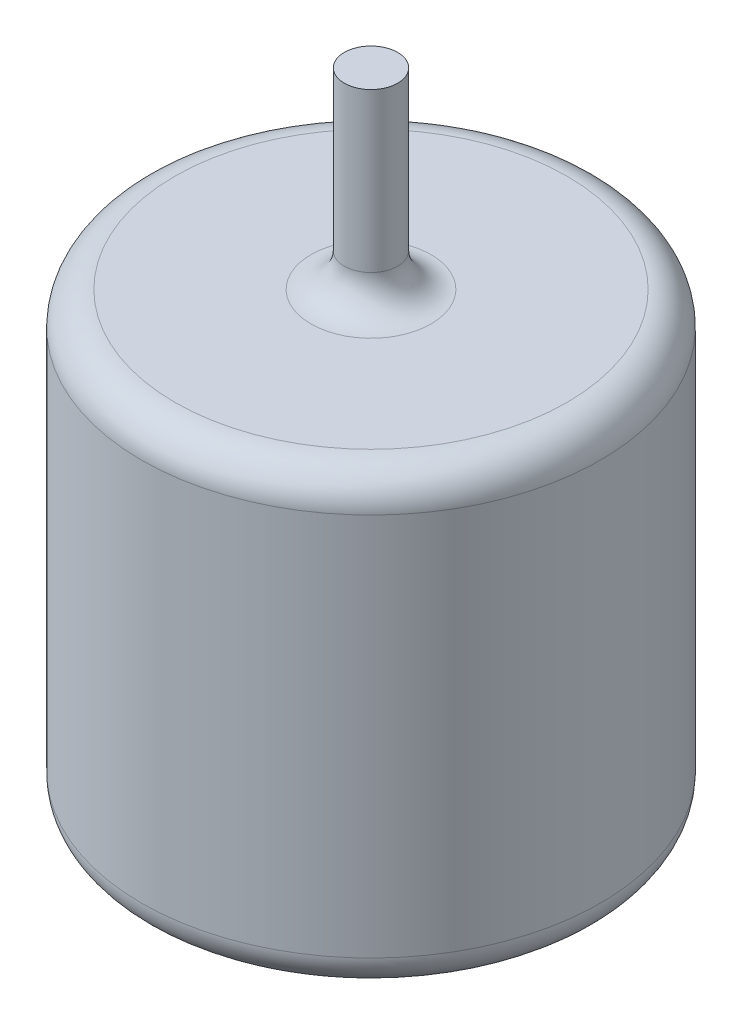
SolidWorks part; units mm, degrees
ref_plane "Alzado" through (0, 0, 0) normal (0, 0, 1) x (1, 0, 0)
ref_plane "Planta" through (0, 0, 0) normal (0, 1, 0) x (1, 0, 0)
ref_plane "Vista lateral" through (0, 0, 0) normal (1, 0, 0) x (0, 0, -1)
sketch "Croquis1" plane through (0, 0, 0) normal (0, 1, 0) x (1, 0, 0)
  circle A0 centre (0, 0) radius 13.75
extrude "Saliente-Extruir1" add sketch "Croquis1" along normal blind 27
sketch "Croquis3" plane through (0, 27, 0) normal (0, 1, 0) x (1, 0, 0)
  circle A0 centre (0, 0) radius 1.6
extrude "Saliente-Extruir2" add sketch "Croquis3" along normal blind 11.5
fillet "Redondeo1" radius 2 3 edges at (0, 0, 13.75) (0, 27, 13.75) (0, 27, 1.6)
